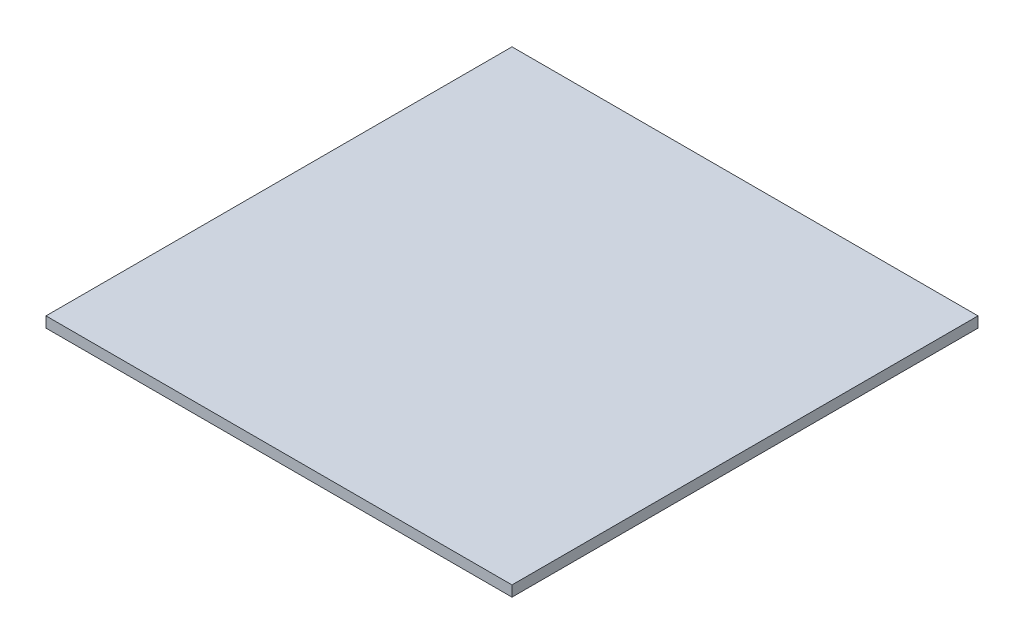
SolidWorks part; units mm, degrees
material "Glass"
ref_plane "Front Plane" through (0, 0, 0) normal (0, 0, 1) x (1, 0, 0)
ref_plane "Top Plane" through (0, 0, 0) normal (0, 1, 0) x (1, 0, 0)
ref_plane "Right Plane" through (0, 0, 0) normal (1, 0, 0) x (0, 0, -1)
sketch "Sketch1" plane through (0, 0, 0) normal (0, 1, 0) x (1, 0, 0)
  line L1 (109.5, -109.5) -> (109.5, 109.5)
  line L2 (109.5, 109.5) -> (-109.5, 109.5)
  line L3 (-109.5, 109.5) -> (-109.5, -109.5)
  line L4 (-109.5, -109.5) -> (109.5, -109.5)
  circle A0 centre (0, 0) radius 109.5 construction
extrude "Boss-Extrude1" add sketch "Sketch1" along normal blind 5
